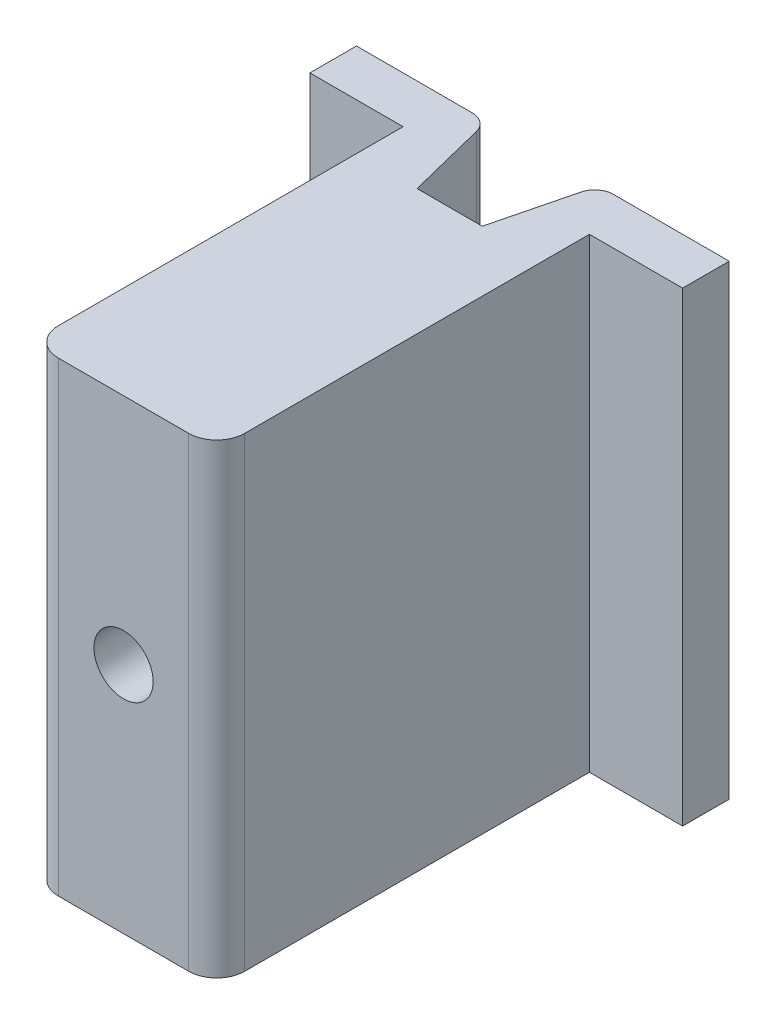
SolidWorks part; units mm, degrees
ref_plane "Alzado" through (0, 0, 0) normal (0, 0, 1) x (1, 0, 0)
ref_plane "Planta" through (0, 0, 0) normal (0, 1, 0) x (1, 0, 0)
ref_plane "Vista lateral" through (0, 0, 0) normal (1, 0, 0) x (0, 0, -1)
sketch "Croquis1" plane through (0, 0, 0) normal (0, 0, 1) x (1, 0, 0)
  line L1 (-20, -25) -> (20, -25)
  line L2 (-20, -25) -> (-20, 25)
  line L3 (-20, 25) -> (20, 25)
  line L4 (20, -25) -> (20, 25)
  line L5 (-20, -25) -> (20, 25) construction
  line L6 (-20, 25) -> (20, -25) construction
  point P0 (0, 0)
  dimension "D1" = 40
  dimension "D2" = 50
extrude "Saliente-Extruir1" add sketch "Croquis1" along normal blind 5
sketch "Croquis2" plane through (0, 0, 5) normal (0, 0, 1) x (1, 0, 0)
  line L0 (20, 25) -> (-20, 25) construction
  line L1 (-10, -25) -> (10, -25)
  line L2 (-10, -25) -> (-10, 25)
  line L3 (-10, 25) -> (10, 25)
  line L4 (10, -25) -> (10, 25)
  line L5 (-10, -25) -> (10, 25) construction
  line L6 (-10, 25) -> (10, -25) construction
  line L7 (-20, 25) -> (-20, -25) construction
  line L8 (20, -25) -> (20, 25) construction
  point P0 (0, 0)
  dimension "D1" = 10
  dimension "D2" = 10
extrude "Saliente-Extruir2" add sketch "Croquis2" along normal blind 40
sketch "Croquis3" plane through (0, 25, 0) normal (0, 1, 0) x (1, 0, 0)
  line L0 (-6, 0) -> (-3.5, -10)
  line L1 (20, 0) -> (-20, 0) construction
  line L2 (-3.5, -10) -> (3.5, -10)
  line L3 (3.5, -10) -> (6, 0)
  line L4 (6, 0) -> (-6, 0)
  point P7 (0, -10)
  dimension "D1" = 4
  dimension "D2" = 4
  dimension "D3" = 7
  dimension "D4" = 10
extrude "Cortar-Extruir1" cut sketch "Croquis3" against normal up to next
fillet "Redondeo1" radius 2 2 edges at (6, 0, 0) (-6, 0, 0)
sketch "Croquis4" plane through (0, 0, 45) normal (0, 0, 1) x (1, 0, 0)
  circle A0 centre (0, 0) radius 3.175
  dimension "D1" = 6.35
extrude "Cortar-Extruir2" cut sketch "Croquis4" against normal up to next
fillet "Redondeo2" radius 3 2 edges at (10, 0, 45) (-10, 0, 45)
